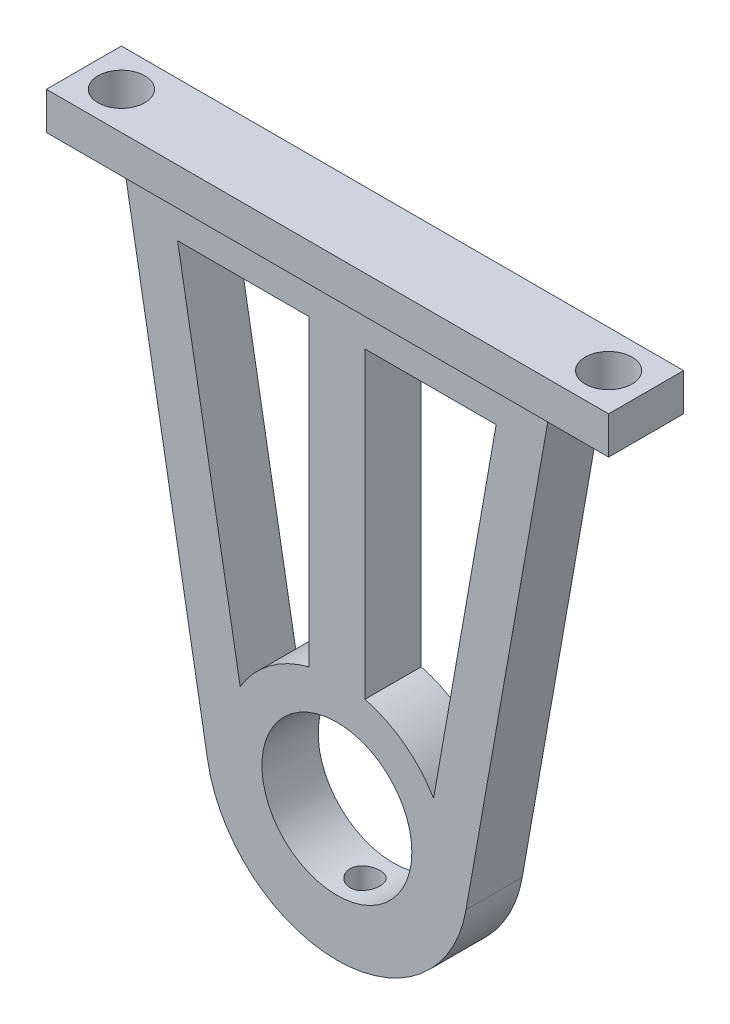
SolidWorks part; units mm, degrees
ref_plane "前视基准面" through (0, 0, 0) normal (0, 0, 1) x (1, 0, 0)
ref_plane "上视基准面" through (0, 0, 0) normal (0, 1, 0) x (1, 0, 0)
ref_plane "右视基准面" through (0, 0, 0) normal (1, 0, 0) x (0, 0, -1)
other "Configuration Table"
sketch "草图1" plane through (0, 0, 0) normal (0, 0, 1) x (1, 0, 0)
  line L0 (0, 0) -> (0, 20.6654) construction
  line L4 (11.3398, 24) -> (6.8937, -1.2155)
  line L5 (-11.3398, 24) -> (-6.8937, -1.2155)
  line L8 (-11.3398, 24) -> (11.3398, 24)
  circle A0 centre (0, 0) radius 4
  arc A1 (-6.8937, -1.2155) -> (6.8937, -1.2155) centre (0, 0) ccw
  dimension "D1" = 8
  dimension "D2" = 14
  dimension "D3" = 24
  dimension "D4" = 10
extrude "凸台-拉伸1" add sketch "草图1" along normal mid plane 3
sketch "草图2" plane through (0, 24, 0) normal (0, 1, 0) x (1, 0, 0)
  line L1 (15, -2) -> (-15, -2)
  line L2 (15, -2) -> (15, 2)
  line L3 (15, 2) -> (-15, 2)
  line L4 (-15, -2) -> (-15, 2)
  line L5 (15, -2) -> (-15, 2) construction
  line L6 (15, 2) -> (-15, -2) construction
  point P0 (0, 0)
  dimension "D1" = 4
  dimension "D2" = 30
extrude "凸台-拉伸2" add sketch "草图2" along normal blind 2
hole_wizard "M3 螺纹孔1" positions "草图6" profile "草图4" tap size "M3" standard "GB"
sketch "草图6" plane through (0, 26, 0) normal (0, 1, 0) x (1, 0, 0)
  line L0 (-13, 0) -> (13, 0) construction
  point P0 (-13, 0)
  point P2 (13, 0)
  point P10 (0, 0)
  dimension "D1" = 26
sketch "草图4" plane through (-13, 26, 0) normal (1, 0, 0) x (0, 0, 1)
  line L0 (0, 0) -> (0, 2.7511)
  line L1 (0, 2.7511) -> (1.25, 2)
  line L2 (1.25, 2) -> (1.25, 0)
  line L5 (1.25, 0) -> (0, 0)
  line L10 (0, 2.7511) -> (-1.25, 2) construction
  line L11 (0, -6.35) -> (0, 107.95) construction
  dimension "螺纹孔钻头直径" = 2.5
  dimension "螺纹孔钻头深度" = 2
  dimension "导头角度" = 118
cosmetic thread "孔螺蚊线1" parameters "D1"=1.5, "D2"=3
cosmetic thread "孔螺蚊线2" parameters "D1"=1.5, "D2"=3
sketch "草图8" plane through (0, 0, -1.5) normal (0, 0, -1) x (-1, 0, 0)
  line L0 (-8.5, 22) -> (8.5, 22)
  line L1 (0, 0) -> (0, 22) construction
  line L2 (-8.5, 22) -> (-5.1605, 3.0609)
  line L3 (8.5, 22) -> (5.1605, 3.0609)
  line L4 (-6.8937, -1.2155) -> (-11.3398, 24) construction
  line L5 (-11.3398, 24) -> (11.3398, 24) construction
  line L6 (-1.5, 22) -> (-1.5, 5.8095)
  line L7 (1.5, 22) -> (1.5, 5.8095)
  circle A0 centre (0, 0) radius 6
  dimension "D3" = 12
  dimension "D1" = 17
  dimension "D2" = 2
  dimension "D4" = 3
extrude "切除-拉伸2" cut sketch "草图8" against normal blind 10 contours A0 L6 L0 L2 | A0 L3 L0 L7
hole_wizard "M2 螺纹孔1" positions "3D草图1" profile "草图11" tap size "M2" standard "GB"
sketch3d "3D草图1"
  point P0 (0, -7, 0)
sketch "草图11" plane through (0, -7, 0) normal (1, 0, 0) x (0, 0, -1)
  line L0 (0, 0) -> (0, 4.6807)
  line L1 (0, 4.6807) -> (0.8, 4.2)
  line L2 (0.8, 4.2) -> (0.8, 0)
  line L5 (0.8, 0) -> (0, 0)
  line L10 (0, 4.6807) -> (-0.8, 4.2) construction
  line L11 (0, -6.35) -> (0, 107.95) construction
  dimension "螺纹孔钻头直径" = 1.6
  dimension "螺纹孔钻头深度" = 4.2
  dimension "导头角度" = 118
cosmetic thread "孔螺蚊线4"
